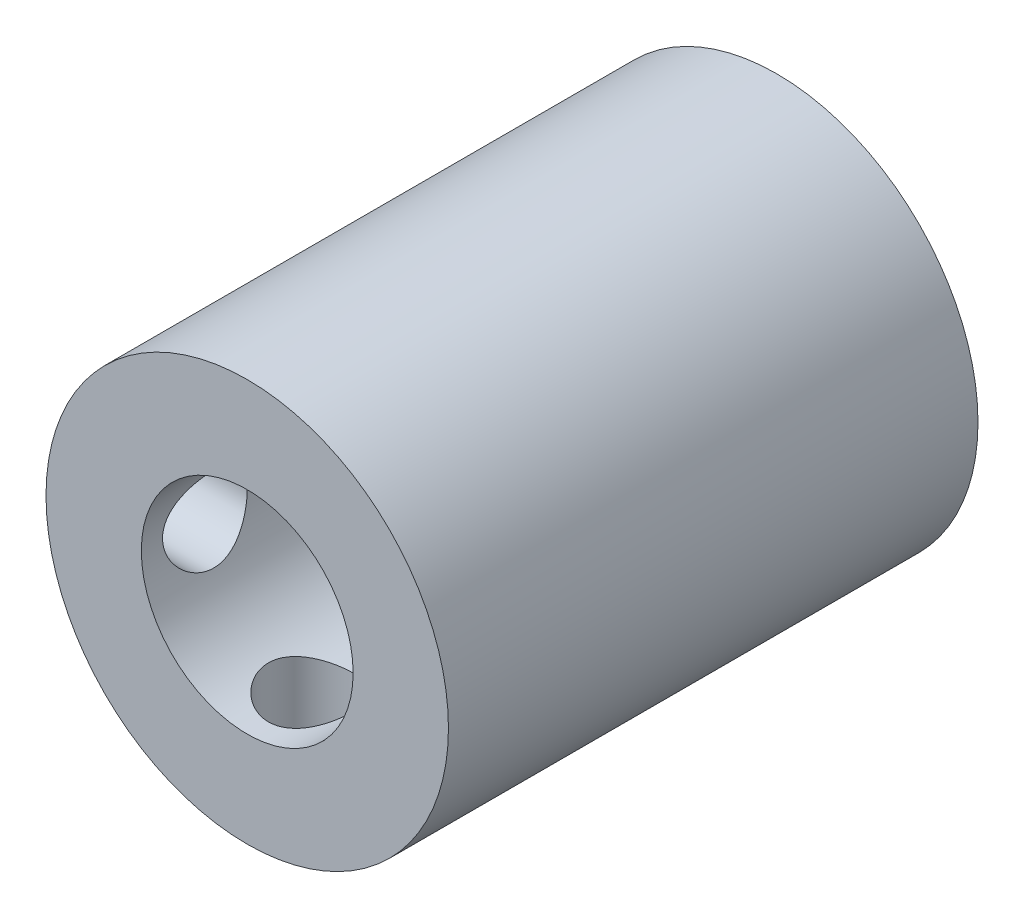
SolidWorks part; units mm, degrees
ref_plane "Front Plane" through (0, 0, 0) normal (0, 0, 1) x (1, 0, 0)
ref_plane "Top Plane" through (0, 0, 0) normal (0, 1, 0) x (1, 0, 0)
ref_plane "Right Plane" through (0, 0, 0) normal (1, 0, 0) x (0, 0, -1)
sketch "Sketch2" plane through (0, 0, 0) normal (0, 0, 1) x (1, 0, 0)
  circle A0 centre (0, 0) radius 9.5
  circle A1 centre (0, 0) radius 2.5
  dimension "D1" = 19
  dimension "D2" = 5
extrude "Boss-Extrude1" add sketch "Sketch2" along normal blind 25
sketch "Sketch3" plane through (0, 0, 25) normal (0, 0, 1) x (1, 0, 0)
  circle A0 centre (0, 0) radius 5
  dimension "D1" = 10
extrude "Cut-Extrude1" cut sketch "Sketch3" against normal blind 16.5
sketch "Sketch4" plane through (-15.414, 54.9081, -53.9702) normal (1, 0, 0) x (0, 1, 0)
  line L0 (-54.9081, 53.9702) -> (-54.9081, 54.9702)
  line L1 (-54.9081, 54.9702) -> (-54.9081, 58.9702)
  line L2 (-54.9081, 78.9702) -> (-54.9081, 77.9702)
  line L3 (-45.4081, 78.9702) -> (-64.4081, 78.9702) construction
  line L4 (-54.9081, 77.9702) -> (-54.9081, 73.9702)
  circle A0 centre (-54.9081, 56.9702) radius 2
  circle A1 centre (-54.9081, 75.9702) radius 2
  dimension "D1" = 1
  dimension "D2" = 4
  dimension "D3" = 1
  dimension "D4" = 4
extrude "Cut-Extrude2" cut sketch "Sketch4" along normal blind 16.5 contours L1 A0 | L1 A0 | L4 A1 | L4 A1
ref_plane "Plane1" through (-15.414, -10.0919, -53.9702) normal (0, -1, 0) x (1, 0, 0)
sketch "Sketch5" plane through (-15.414, -10.0919, -53.9702) normal (0, -1, 0) x (1, 0, 0)
  line L0 (15.414, 53.9702) -> (15.414, 54.9702)
  line L1 (5.914, 53.9702) -> (24.914, 53.9702) construction
  line L2 (15.414, 54.9702) -> (15.414, 58.9702)
  line L3 (24.914, 66.4702) -> (22.6019, 66.4702)
  line L4 (24.914, 53.9702) -> (24.914, 78.9702) construction
  circle A0 centre (15.414, 56.9702) radius 2
  circle A1 centre (15.414, 75.9702) radius 2
  dimension "D1" = 1
  dimension "D2" = 4
extrude "Cut-Extrude3" cut sketch "Sketch5" against normal blind 9.5 contours L2 A0 | L2 A0 | A1
